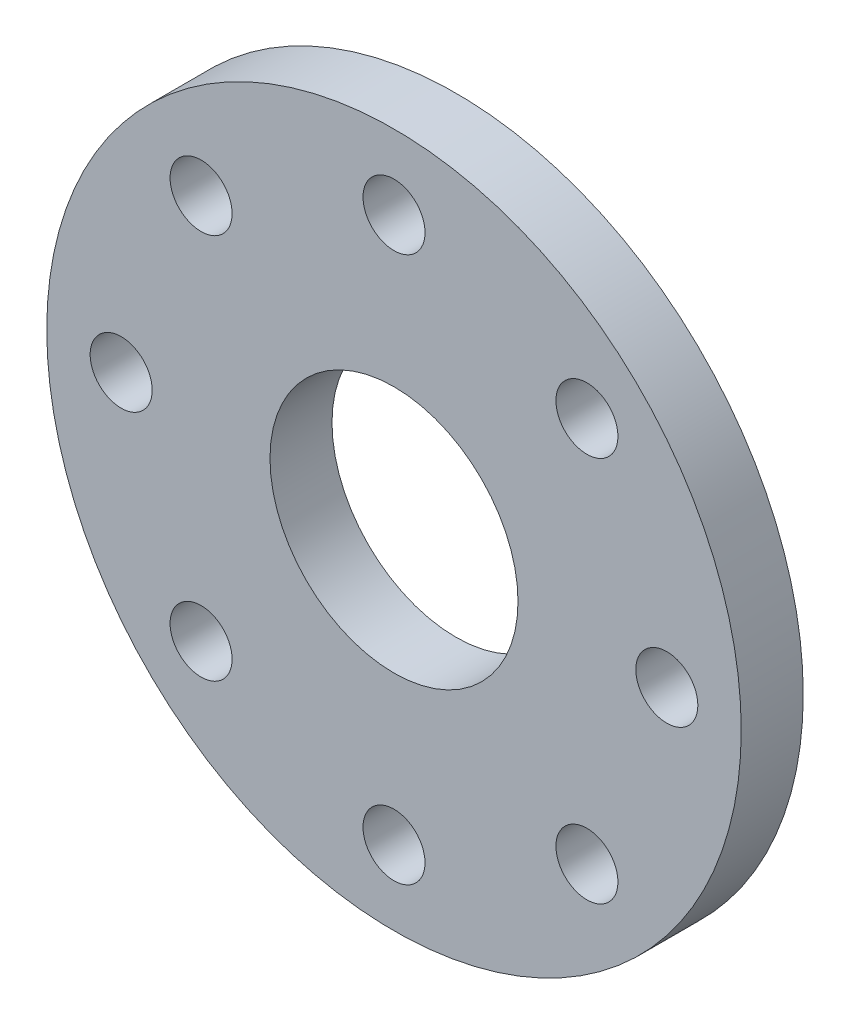
SolidWorks part; units mm, degrees
ref_plane "Plano frontal" through (0, 0, 0) normal (0, 0, 1) x (1, 0, 0)
ref_plane "Plano superior" through (0, 0, 0) normal (0, 1, 0) x (1, 0, 0)
ref_plane "Plano direito" through (0, 0, 0) normal (1, 0, 0) x (0, 0, -1)
sketch "Esboço1" plane through (0, 0, 0) normal (0, 0, 1) x (1, 0, 0)
  circle A0 centre (0, 0) radius 14
  circle A1 centre (0, 0) radius 5
  circle A2 centre (0, 11) radius 1.25
  circle A3 centre (7.7782, 7.7782) radius 1.25
  circle A4 centre (11, 0) radius 1.25
  circle A5 centre (7.7782, -7.7782) radius 1.25
  circle A6 centre (0, -11) radius 1.25
  circle A7 centre (-7.7782, -7.7782) radius 1.25
  circle A8 centre (-11, 0) radius 1.25
  circle A9 centre (-7.7782, 7.7782) radius 1.25
  point P22 (0, 0)
  dimension "D1" = 28
  dimension "D2" = 10
  dimension "D3" = 2.5
  dimension "D4" = 11
  dimension "D5" = 8
extrude "Ressalto-extrusão1" add sketch "Esboço1" along normal blind 2.5
